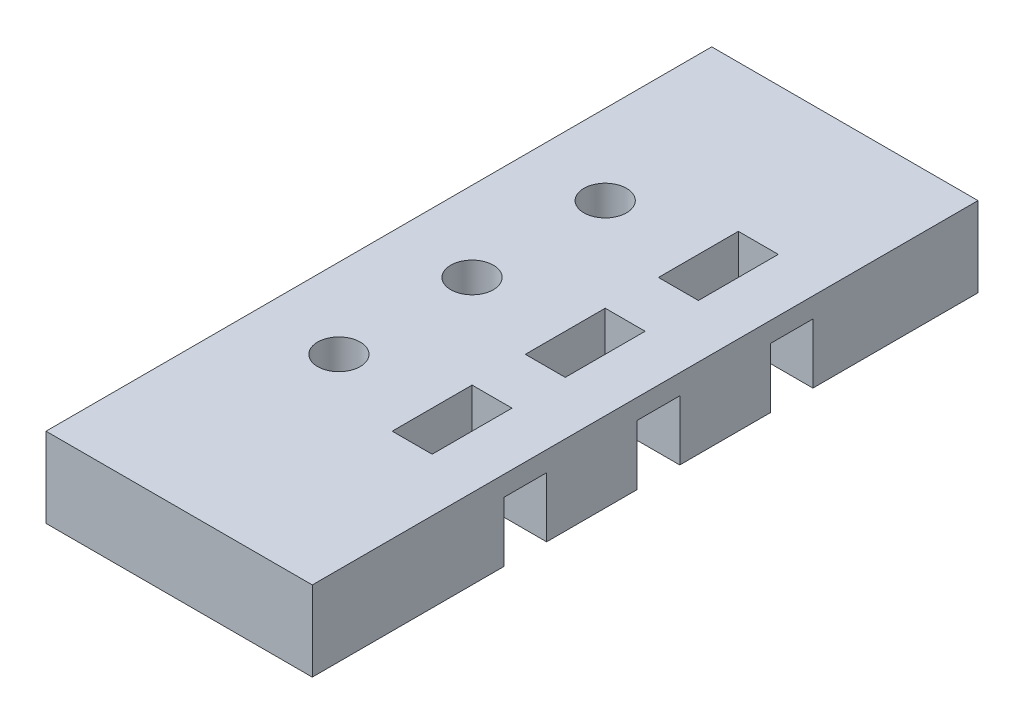
SolidWorks part; units mm, degrees
ref_plane "前视基准面" through (0, 0, 0) normal (0, 0, 1) x (1, 0, 0)
ref_plane "上视基准面" through (0, 0, 0) normal (0, 1, 0) x (1, 0, 0)
ref_plane "右视基准面" through (0, 0, 0) normal (1, 0, 0) x (0, 0, -1)
other "Configuration Table"
sketch "草图1" plane through (0, 0, 0) normal (0, 1, 0) x (1, 0, 0)
  line L1 (0, 0) -> (20, 0)
  line L2 (0, 0) -> (0, 50)
  line L3 (0, 50) -> (20, 50)
  line L4 (20, 0) -> (20, 50)
  dimension "D1" = 20
  dimension "D2" = 50
extrude "凸台-拉伸1" add sketch "草图1" along normal blind 6
sketch "草图3" plane through (0, 0, 0) normal (0, -1, 0) x (1, 0, 0)
  line L0 (20, 0) -> (20, -50) construction
  line L1 (20, -27.6) -> (16, -27.6)
  line L2 (20, -27.6) -> (20, -24.4)
  line L3 (20, -24.4) -> (16, -24.4)
  line L4 (16, -27.6) -> (16, -24.4)
  line L6 (20, -14.4) -> (16, -14.4)
  line L7 (16, -17.6) -> (16, -14.4)
  line L8 (20, -17.6) -> (20, -14.4)
  line L9 (20, -17.6) -> (16, -17.6)
  line L10 (16, -37.6) -> (16, -34.4)
  line L11 (20, -34.4) -> (16, -34.4)
  line L12 (20, -37.6) -> (20, -34.4)
  line L13 (20, -37.6) -> (16, -37.6)
  line L14 (20, -26) -> (50020, -26) construction
  line L15 (0, 0) -> (20, 0) construction
  point P8 (20, -26)
  dimension "D1" = 26
  dimension "D2" = 3.2
  dimension "D3" = 4
  dimension "D4" = 2
  dimension "D5" = 2
extrude "切除-拉伸1" cut sketch "草图3" against normal blind 4.5
sketch "草图5" plane through (0, 0, 0) normal (0, -1, 0) x (1, 0, 0)
  line L1 (16, -39) -> (13, -39)
  line L2 (16, -39) -> (16, -33)
  line L3 (16, -33) -> (13, -33)
  line L4 (13, -39) -> (13, -33)
  line L5 (20, -34.4) -> (16, -34.4) construction
  line L6 (16, -34.4) -> (16, -37.6) construction
  line L7 (13, -29) -> (13, -23)
  line L8 (16, -29) -> (16, -23)
  line L9 (16, -29) -> (13, -29)
  line L10 (16, -23) -> (13, -23)
  line L11 (13, -19) -> (13, -13)
  line L12 (16, -19) -> (16, -13)
  line L13 (16, -19) -> (13, -19)
  line L14 (16, -13) -> (13, -13)
  line L17 (0, 0) -> (20, 0) construction
  line L18 (20, 0) -> (20, -14.4) construction
  circle A3 centre (6, -16) radius 1.6
  circle A4 centre (6, -26) radius 1.6
  circle A5 centre (6, -36) radius 1.6
  dimension "D5" = 3.2
  dimension "D7" = 14
  dimension "D8" = 16
  dimension "D1" = 3
  dimension "D2" = 1.4
  dimension "D3" = 6
  dimension "D4" = 3
  dimension "D6" = 3
extrude "切除-拉伸2" cut sketch "草图5" against normal blind 14.5
sketch "草图7" plane through (0, 0, 0) normal (0, -1, 0) x (1, 0, 0)
  circle A0 centre (6, -16) radius 3.5
  circle A1 centre (6, -26) radius 3.5
  circle A2 centre (6, -36) radius 3.5
  dimension "D1" = 7
  dimension "D2" = 3
extrude "切除-拉伸3" cut sketch "草图7" against normal blind 3
